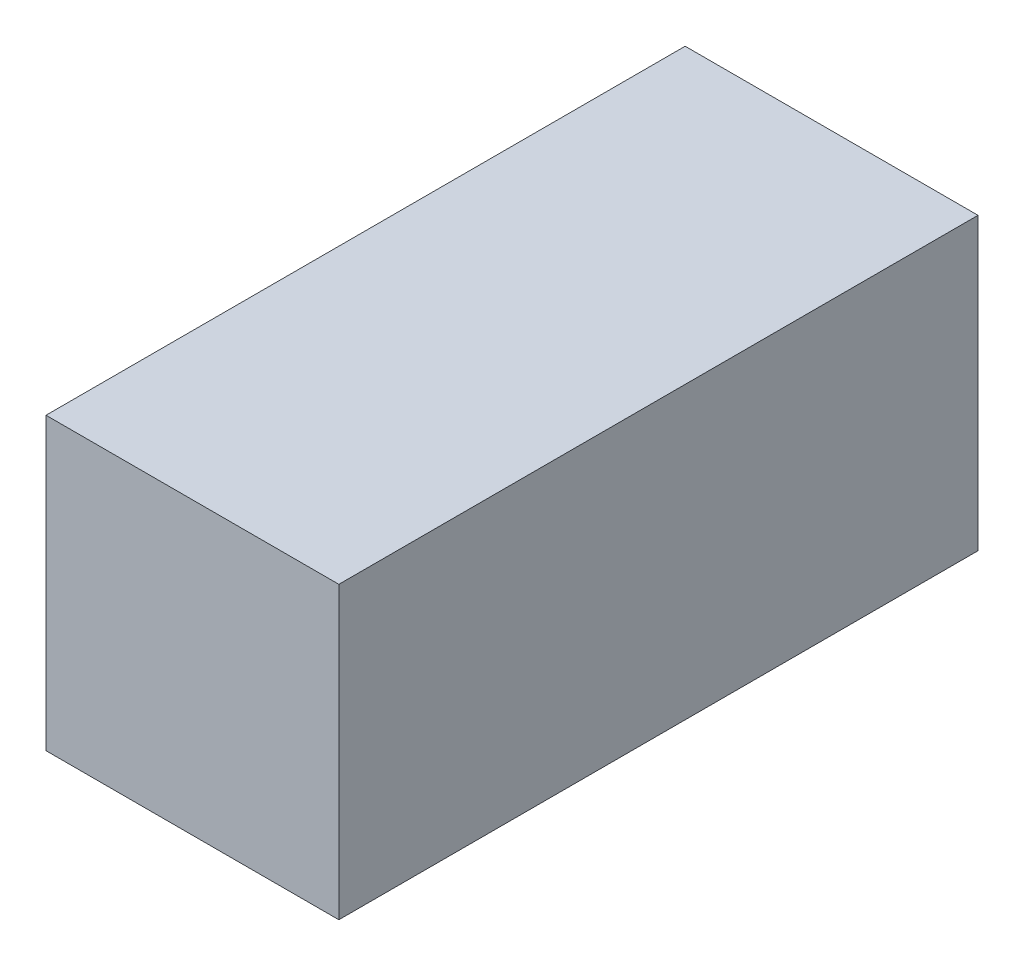
SolidWorks part; units mm, degrees
ref_plane "Front Plane" through (0, 0, 0) normal (0, 0, 1) x (1, 0, 0)
ref_plane "Top Plane" through (0, 0, 0) normal (0, 1, 0) x (1, 0, 0)
ref_plane "Right Plane" through (0, 0, 0) normal (1, 0, 0) x (0, 0, -1)
sketch "Sketch1" plane through (0, 119.9439, 0) normal (0, -1, 0) x (1, 0, 0)
  line L0 (468.4825, -311.3459) -> (468.4825, -136.3459) construction
  line L1 (418.4829, -311.1319) -> (518.482, -311.5599) construction
  line L3 (378.8561, -224.2319) -> (558.8561, -224.2319) construction
  line L5 (558.6528, -271.7315) -> (559.0594, -176.7324) construction
  line L7 (462.1825, -210.0959) -> (474.7825, -210.0959)
  line L8 (462.1825, -210.0959) -> (462.1825, -237.5959)
  line L9 (462.1825, -237.5959) -> (474.7825, -237.5959)
  line L10 (474.7825, -210.0959) -> (474.7825, -237.5959)
  line L11 (462.1825, -210.0959) -> (474.7825, -237.5959) construction
  line L12 (462.1825, -237.5959) -> (474.7825, -210.0959) construction
  point P12 (468.4825, -223.8459)
  point P17 (474.7825, -223.8459)
  dimension "D1" = 27.5
  dimension "D2" = 12.6
extrude "Boss-Extrude1" add sketch "Sketch1" along normal blind 12.5 contours L8 L7 L10 L9
